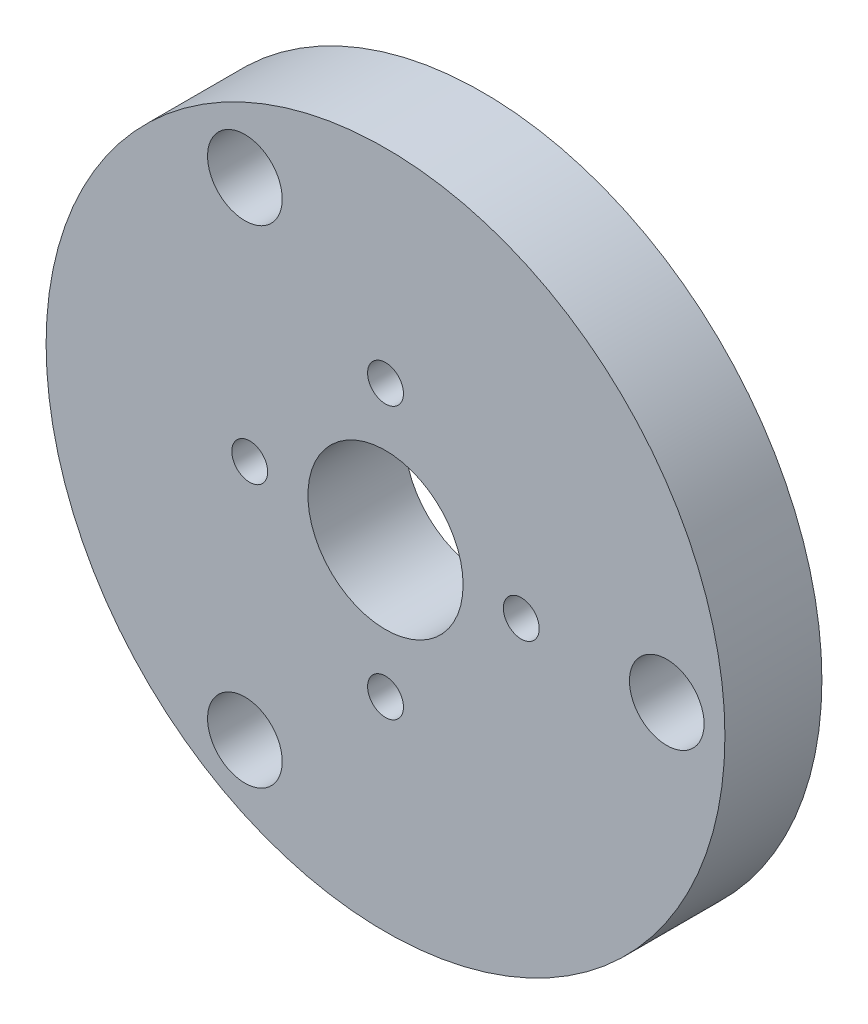
SolidWorks part; units mm, degrees
ref_plane "Plan de face" through (0, 0, 0) normal (0, 0, 1) x (1, 0, 0)
ref_plane "Plan de dessus" through (0, 0, 0) normal (0, 1, 0) x (1, 0, 0)
ref_plane "Plan de droite" through (0, 0, 0) normal (1, 0, 0) x (0, 0, -1)
sketch "Esquisse1" plane through (0, 0, 0) normal (0, 0, 1) x (1, 0, 0)
  line L0 (0, 0) -> (14.5, 0) construction
  circle A0 centre (0, -7) radius 0.925
  circle A1 centre (-7, 0) radius 0.925
  circle A2 centre (0, 7) radius 0.925
  circle A3 centre (-7.25, -12.5574) radius 1.925
  circle A4 centre (-7.25, 12.5574) radius 1.925
  circle A5 centre (0, 0) radius 17.5
  circle A11 centre (0, 0) radius 4
  circle A12 centre (14.5, 0) radius 1.925
  circle A15 centre (7, 0) radius 0.925
  point P10 (0, 0)
  point P14 (0, 0)
  dimension "D1" = 3.85
  dimension "D2" = 1.85
  dimension "D3" = 7
  dimension "D4" = 14.5
  dimension "D5" = 8
  dimension "D8" = 35
  dimension "D6" = 4
  dimension "D7" = 3
extrude "Boss.-Extru.1" add sketch "Esquisse1" along normal blind 5
